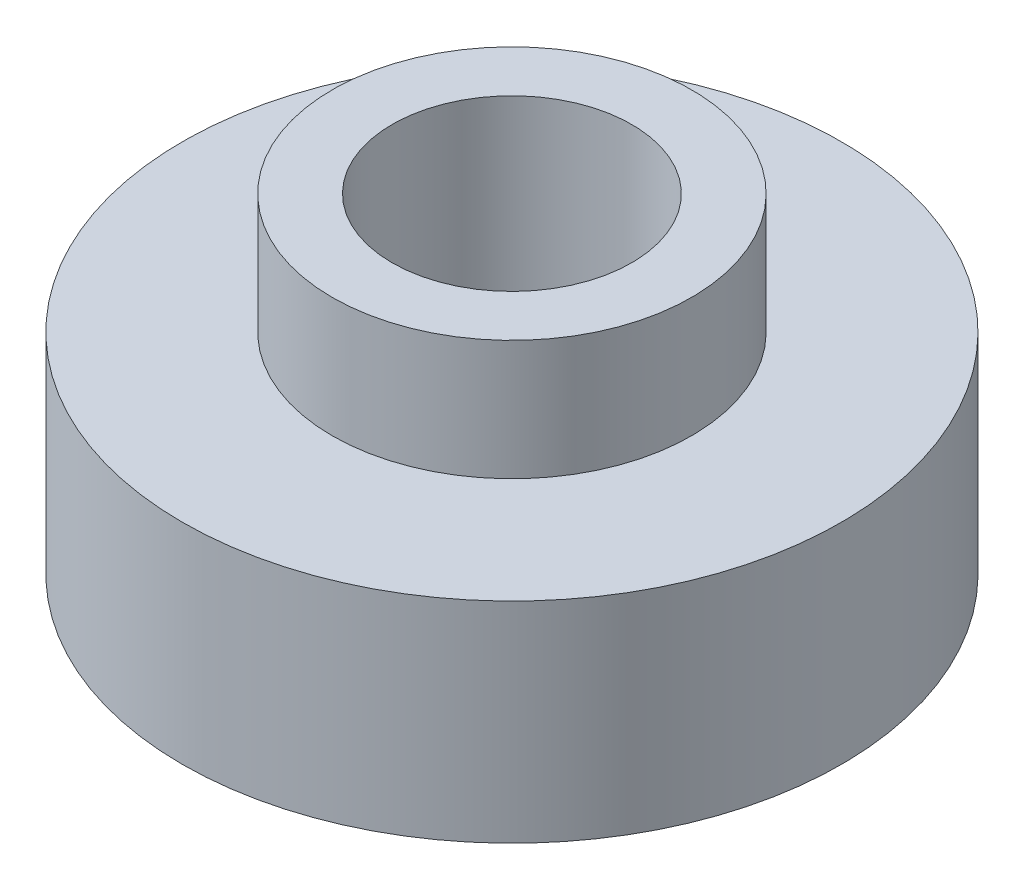
SolidWorks part; units mm, degrees
ref_plane "Front Plane" through (0, 0, 0) normal (0, 0, 1) x (1, 0, 0)
ref_plane "Top Plane" through (0, 0, 0) normal (0, 1, 0) x (1, 0, 0)
ref_plane "Right Plane" through (0, 0, 0) normal (1, 0, 0) x (0, 0, -1)
sketch "Sketch1" plane through (0, 0, 0) normal (0, 1, 0) x (1, 0, 0)
  circle A0 centre (0, 0) radius 11
  dimension "D1" = 22
extrude "Boss-Extrude1" add sketch "Sketch1" along normal blind 7
sketch "Sketch2" plane through (0, 7, 0) normal (0, 1, 0) x (1, 0, 0)
  circle A0 centre (0, 0) radius 6
  dimension "D1" = 12
extrude "Boss-Extrude2" add sketch "Sketch2" along normal blind 4
sketch "Sketch3" plane through (0, 11, 0) normal (0, 1, 0) x (1, 0, 0)
  circle A0 centre (0, 0) radius 4
  dimension "D1" = 8
extrude "Cut-Extrude1" cut sketch "Sketch3" against normal up to next
